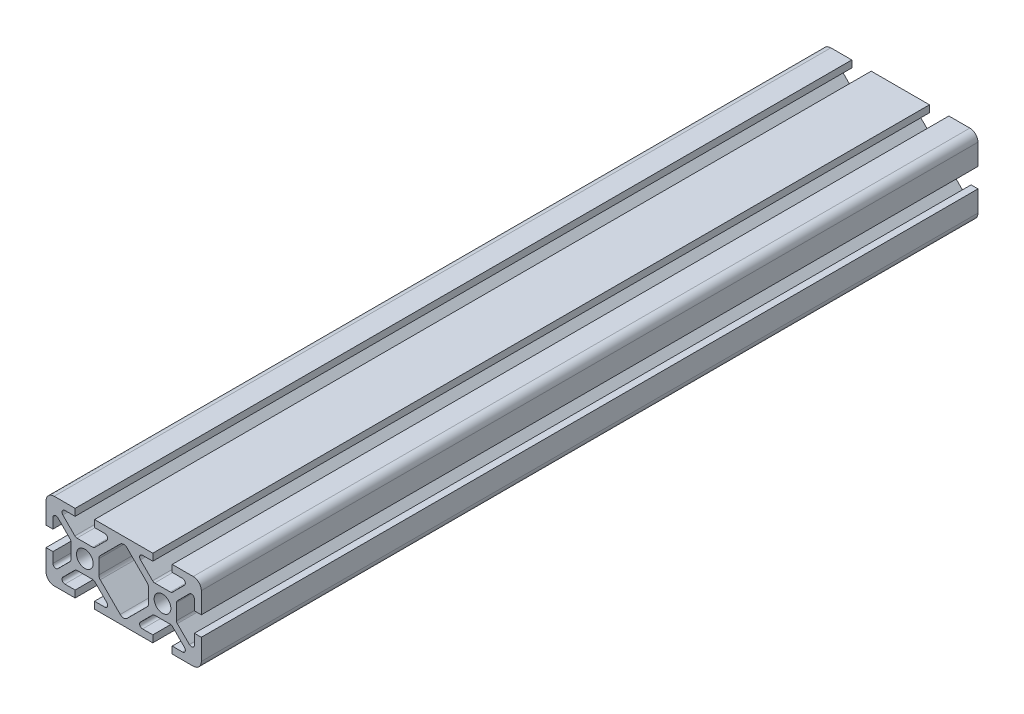
SolidWorks part; units mm, degrees
ref_plane "Front Plane" through (0, 0, 0) normal (0, 0, 1) x (1, 0, 0)
ref_plane "Top Plane" through (0, 0, 0) normal (0, 1, 0) x (1, 0, 0)
ref_plane "Right Plane" through (0, 0, 0) normal (1, 0, 0) x (0, 0, -1)
sketch "Sketch1" plane through (0, 0, 0) normal (0, 0, 1) x (1, 0, 0)
  line L0 (10, 10) -> (10, -10) construction
  line L1 (-20, 0) -> (20, 0) construction
  line L2 (12.5, -10) -> (20, -10)
  line L3 (20, -10) -> (20, -2.5)
  line L4 (12.5, -10) -> (12.5, -8.2134)
  line L5 (12.5, -8.2134) -> (16.95, -8.2134)
  line L6 (16.95, -8.2134) -> (12.3366, -3.6)
  line L7 (10, 0) -> (20, -10) construction
  line L8 (20, -2.5) -> (18.2134, -2.5)
  line L9 (18.2134, -2.5) -> (18.2134, -6.95)
  line L10 (18.2134, -6.95) -> (13.6, -2.3366)
  line L11 (15.9067, -4.6433) -> (14.6433, -5.9067) construction
  line L12 (0, 10) -> (0, -10) construction
  line L13 (0, -10) -> (-20, -10) construction
  line L14 (-10, 10) -> (10, 10) construction
  line L15 (20, 2.5) -> (20, -2.5) construction
  circle A0 centre (10, 0) radius 2.15
  arc A1 (15.5015, -8.2134) -> (15.9257, -7.1891) centre (15.5015, -7.6134) ccw construction
  point P8 (10, -3.6)
  point P16 (15.275, -5.275)
  point P30 (20, 0)
  dimension "Center Hole Diameter" = 4.3
  dimension "D3" = 0.6
  dimension "Rail Width" = 20
  dimension "T-Slot Width" = 5
  dimension "Slot Depth" = 6.4
  dimension "Rail Height" = 40
  dimension "Inner Slot Width" = 13.9
  dimension "Hole Spacing" = 20
sketch "Sketch2" plane through (0, 0, 0) normal (1, 0, 0) x (0, 0, -1)
  line L0 (-100, -10) -> (100, -10) construction
  line L1 (-60, 0) -> (60, 0) construction
  point P6 (-60, 0)
  point P8 (60, 0)
  dimension "Length" = 200
  dimension "D1" = 40
sketch "Sketch3" plane through (0, 0, 0) normal (0, 0, 1) x (1, 0, 0)
  line L0 (12.5, -10) -> (17.9, -10)
  line L1 (12.5, -10) -> (20, -10) construction
  line L2 (12.5, -10) -> (12.5, -8.2134) construction
  line L3 (12.5, -8.2134) -> (16.95, -8.2134) construction
  line L4 (12.5, -8.2134) -> (12.5, -10)
  line L5 (12.5, -8.2134) -> (16.95, -8.2134)
  line L6 (10, -3.6) -> (12.3366, -3.6)
  line L7 (16.95, -8.2134) -> (12.3366, -3.6) construction
  line L8 (12.3366, -3.6) -> (16.95, -8.2134)
  line L9 (20, -10) -> (20, -2.5) construction
  line L10 (18.2134, -6.95) -> (13.6, -2.3366) construction
  line L11 (18.2134, -2.5) -> (18.2134, -6.95) construction
  line L12 (18.2134, -6.95) -> (18.2134, -2.5)
  line L13 (20, -2.5) -> (18.2134, -2.5) construction
  line L14 (18.2134, -2.5) -> (20, -2.5)
  line L15 (20, -2.5) -> (20, -7.9)
  line L16 (18.2134, -6.95) -> (13.6, -2.3366)
  line L17 (13.6, 0) -> (13.6, -2.3366)
  line L18 (-20, 0) -> (20, 0) construction
  line L19 (10, -3.6) -> (10, -2.15)
  line L20 (10, 10) -> (10, -10) construction
  line L21 (13.6, 0) -> (12.15, 0)
  arc A5 (17.9, -10) -> (20, -7.9) centre (17.9, -7.9) ccw
  circle A10 centre (10, 0) radius 2.15 construction
  arc A11 (10, -2.15) -> (12.15, 0) centre (10, 0) ccw
  dimension "D1" = 2.1
extrude "Boss-Extrude1" add sketch "Sketch3" along normal mid plane 200
sketch "Sketch4" plane through (0, 0, 0) normal (0, 0, 1) x (1, 0, 0)
  line L0 (10, -3.6) -> (7.6634, -3.6)
  line L4 (7.6634, -3.6) -> (3.05, -8.2134)
  line L5 (3.05, -8.2134) -> (7.5, -8.2134)
  line L6 (7.5, -8.2134) -> (7.5, -10)
  line L18 (7.5, -10) -> (0, -10)
  line L19 (12.5, -10) -> (12.5, -8.2134) construction
  line L20 (12.5, -8.2134) -> (16.95, -8.2134) construction
  line L21 (10, -3.6) -> (12.3366, -3.6) construction
  line L22 (16.95, -8.2134) -> (12.3366, -3.6) construction
  line L23 (0, -8.7366) -> (6.4, -2.3366)
  line L24 (0, 10) -> (0, -10) construction
  line L25 (6.4, -2.3366) -> (6.4, 0)
  line L26 (-20, 0) -> (20, 0) construction
  line L27 (6.4, 0) -> (7.85, 0)
  line L28 (13.6, 0) -> (12.15, 0) construction
  line L29 (0, -8.7366) -> (0, -10)
  line L30 (10, -2.15) -> (10, -3.6)
  circle A4 centre (10, 0) radius 2.15 construction
  arc A5 (7.85, 0) -> (10, -2.15) centre (10, 0) ccw
extrude "Boss-Extrude2" add sketch "Sketch4" along normal mid plane 200
mirror "Mirror1" about plane through (0, 0, 0) normal (1, 0, 0) of bodies 137 134
mirror "Mirror2" about plane through (0, 0, 0) normal (0, 1, 0) of bodies 135
fillet "Fillet1" radius 0.75 24 edges at (-7.6634, -3.6, 0) (-12.3366, -3.6, 0) (12.3366, -3.6, 0) (7.6634, -3.6, 0) (-3.05, -8.2134, 0) (-18.2134, -6.95, 0) (-16.95, -8.2134, 0) (-13.6, -2.3366, 0) (-18.2134, 6.95, 0) (-16.95, 8.2134, 0) (-12.3366, 3.6, 0) (-7.6634, 3.6, 0) (-13.6, 2.3366, 0) (-3.05, 8.2134, 0) (3.05, 8.2134, 0) (13.6, -2.3366, 0) (18.2134, 6.95, 0) (13.6, 2.3366, 0) (7.6634, 3.6, 0) (12.3366, 3.6, 0) (16.95, 8.2134, 0) (18.2134, -6.95, 0) (16.95, -8.2134, 0) (3.05, -8.2134, 0)
fillet "Fillet2" radius 1.25 6 edges at (0, -8.7366, 0) (-6.4, -2.3366, 0) (0, 8.7366, 0) (-6.4, 2.3366, 0) (6.4, -2.3366, 0) (6.4, 2.3366, 0)
equation "\"D1@Sketch3\" = \"D3@Sketch1\" * 3.5"
equation "\"D1@Boss-Extrude1\" = \"Length@Sketch2\""
equation "\"D1@Boss-Extrude2\" = \"Length@Sketch2\""
equation "\"D1@Sketch2\"=\"Rail Height@Sketch1\""
